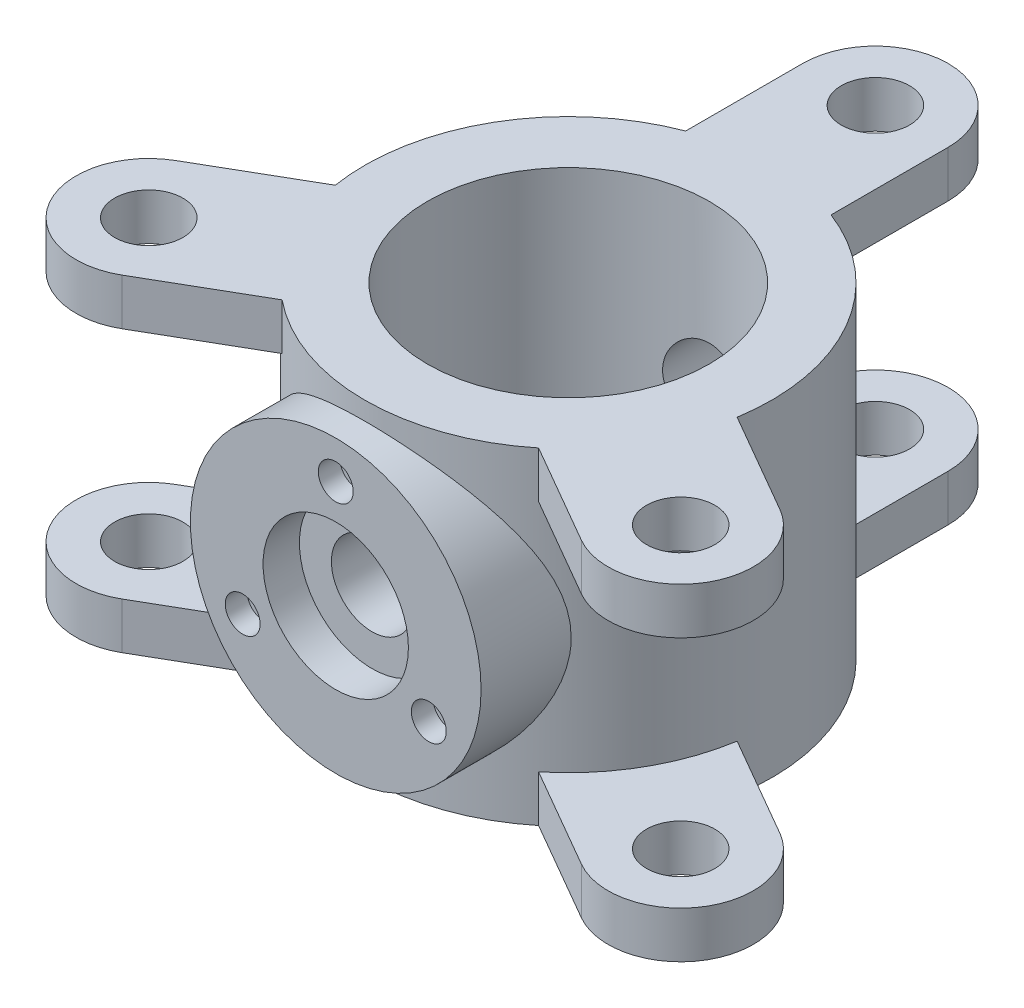
SolidWorks part; units mm, degrees
ref_plane "Front Plane" through (0, 0, 0) normal (0, 0, 1) x (1, 0, 0)
ref_plane "Top Plane" through (0, 0, 0) normal (0, 1, 0) x (1, 0, 0)
ref_plane "Right Plane" through (0, 0, 0) normal (1, 0, 0) x (0, 0, -1)
sketch "Sketch1" plane through (0, 0, 0) normal (0, 1, 0) x (1, 0, 0)
  circle A0 centre (0, 0) radius 97
  circle A1 centre (0, 0) radius 140
  dimension "D1" = 280
  dimension "D2" = 194
extrude "Boss-Extrude3" add sketch "Sketch1" along normal blind 225
sketch "Sketch4" plane through (0, 225, 0) normal (0, 1, 0) x (1, 0, 0)
  line L1 (-50, 211.3036) -> (50, 211.3036) construction
  line L2 (-50, 211.3036) -> (-50, 118.8042)
  line L3 (-50, 118.8042) -> (50, 118.8042)
  line L4 (50, 211.3036) -> (50, 118.8042)
  line L5 (0, 165.0539) -> (3.8905, 161.4552) construction
  line L6 (-3.8905, 161.4552) -> (0, 165.0539) construction
  arc A0 (50, 211.3036) -> (-50, 211.3036) centre (0, 211.3036) ccw
  arc A1 (-3.8905, 161.4552) -> (3.8905, 161.4552) centre (0, 211.3036) ccw
  circle A2 centre (0, 211.3036) radius 23.5
  point P0 (0, 165.0539)
  point P11 (0, 0)
  dimension "D1" = 100
  dimension "D3" = 47
  dimension "D2" = 211.3036
extrude "Boss-Extrude4" add sketch "Sketch4" against normal blind 32
pattern_circular "CirPattern2" count 3 over 360 about axis through (0, 0, 0) along (0, 1, 0) of "Boss-Extrude4"
ref_plane "Plane1" through (0, 112.5, 0) normal (0, 1, 0) x (1, 0, 0)
mirror "Mirror1" about plane through (0, 112.5, 0) normal (0, 1, 0) of "CirPattern2", "Boss-Extrude4"
ref_plane "Plane3" through (0, 0, 160) normal (0, 0, 1) x (1, 0, 0)
sketch "Sketch6" plane through (0, 0, 160) normal (0, 0, 1) x (1, 0, 0)
  line L0 (-88.2475, 0) -> (88.2475, 0) construction
  circle A0 centre (0, 112.5) radius 100
  dimension "D1" = 200
  dimension "D2" = 112.5
extrude "Boss-Extrude5" add sketch "Sketch6" against normal up to next
sketch "Sketch7" plane through (0, 0, 160) normal (0, 0, 1) x (1, 0, 0)
  circle A0 centre (0, 112.5) radius 50
  dimension "D1" = 100
extrude "Cut-Extrude1" cut sketch "Sketch7" against normal blind 25
sketch "Sketch8" plane through (0, 0, 135) normal (0, 0, 1) x (1, 0, 0)
  circle A0 centre (0, 112.5) radius 28
  dimension "D1" = 56
extrude "Cut-Extrude2" cut sketch "Sketch8" against normal through all
sketch "Sketch9" plane through (0, 0, 160) normal (0, 0, 1) x (1, 0, 0)
  circle A0 centre (0, 186.4282) radius 12
  circle A1 centre (0, 112.5) radius 50 construction
  point P4 (0, 0)
  point P7 (0, 0)
  dimension "D1" = 24
  dimension "D2" = 73.9282
extrude "Cut-Extrude3" cut sketch "Sketch9" against normal blind 15
pattern_circular "CirPattern3" count 3 over 360 about axis through (0, 112.5, 0) along (0, 0, 1) of "Cut-Extrude3"
